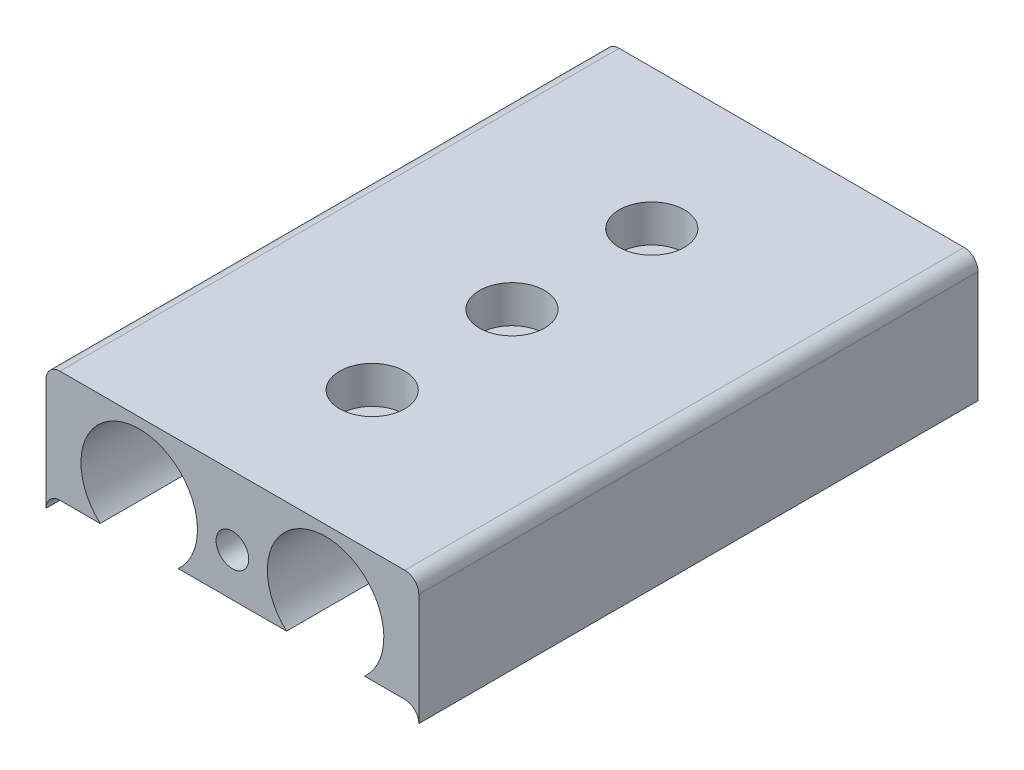
SolidWorks part; units mm, degrees
ref_plane "前视基准面" through (0, 0, 0) normal (0, 0, 1) x (1, 0, 0)
ref_plane "上视基准面" through (0, 0, 0) normal (0, 1, 0) x (1, 0, 0)
ref_plane "右视基准面" through (0, 0, 0) normal (1, 0, 0) x (0, 0, -1)
sketch "草图1" plane through (0, 0, 0) normal (0, 0, 1) x (1, 0, 0)
  line L0 (38.7951, 43.7657) -> (1.7951, 43.7657)
  line L4 (0.2951, 42.2657) -> (0.2951, 30.2657)
  line L5 (40.2951, 42.2657) -> (40.2951, 30.2657)
  line L6 (1.7951, 31.7657) -> (38.7951, 31.7657)
  arc A0 (1.7951, 43.7657) -> (0.2951, 42.2657) centre (1.7951, 42.2657) ccw
  arc A3 (40.2951, 42.2657) -> (38.7951, 43.7657) centre (38.7951, 42.2657) ccw
  circle A4 centre (30.2951, 36.4057) radius 3.5
  circle A6 centre (10.2951, 36.4057) radius 3.5
  arc A8 (1.7951, 31.7657) -> (0.2951, 30.2657) centre (1.7951, 30.2657) ccw
  arc A9 (40.2951, 30.2657) -> (38.7951, 31.7657) centre (38.7951, 30.2657) ccw
extrude "凸台-拉伸1" add sketch "草图1" along normal blind 60
sketch "草图2" plane through (0, 0, 60) normal (0, 0, 1) x (1, 0, 0)
  circle A0 centre (10.2951, 36.4057) radius 6.25
  circle A1 centre (30.2951, 36.4057) radius 6.25
extrude "切除-拉伸1" cut sketch "草图2" against normal blind 20
sketch "草图3" plane through (0, 0, 0) normal (0, 0, -1) x (-1, 0, 0)
  circle A0 centre (-10.2951, 36.4057) radius 6.25
  circle A1 centre (-30.2951, 36.4057) radius 6.25
extrude "切除-拉伸2" cut sketch "草图3" against normal blind 20
sketch "草图4" plane through (0, 43.7657, 0) normal (0, 1, 0) x (1, 0, 0)
  circle A0 centre (20.2951, -30) radius 3.5
extrude "切除-拉伸3" cut sketch "草图4" against normal blind 4
sketch "草图5" plane through (0, 43.7657, 0) normal (0, 1, 0) x (1, 0, 0)
  circle A0 centre (20.2951, -15) radius 3.5
  circle A1 centre (20.2951, -45) radius 3.5
extrude "切除-拉伸4" cut sketch "草图5" against normal blind 4
sketch "草图6" plane through (0, 39.7657, 0) normal (0, 1, 0) x (1, 0, 0)
  circle A0 centre (20.2951, -30) radius 1.75
  circle A1 centre (20.2951, -15) radius 1.75
  circle A2 centre (20.2951, -45) radius 1.75
extrude "切除-拉伸5" cut sketch "草图6" against normal blind 14
sketch "草图7" plane through (0, 0, 60) normal (0, 0, 1) x (1, 0, 0)
  circle A0 centre (20.2951, 36.4057) radius 1.75
extrude "切除-拉伸6" cut sketch "草图7" against normal blind 10
sketch "草图8" plane through (0, 0, 0) normal (0, 0, -1) x (-1, 0, 0)
  circle A0 centre (-20.2951, 36.4057) radius 1.75 construction
  circle A1 centre (-20.2951, 36.4057) radius 1.75
extrude "切除-拉伸7" cut sketch "草图8" against normal blind 10
